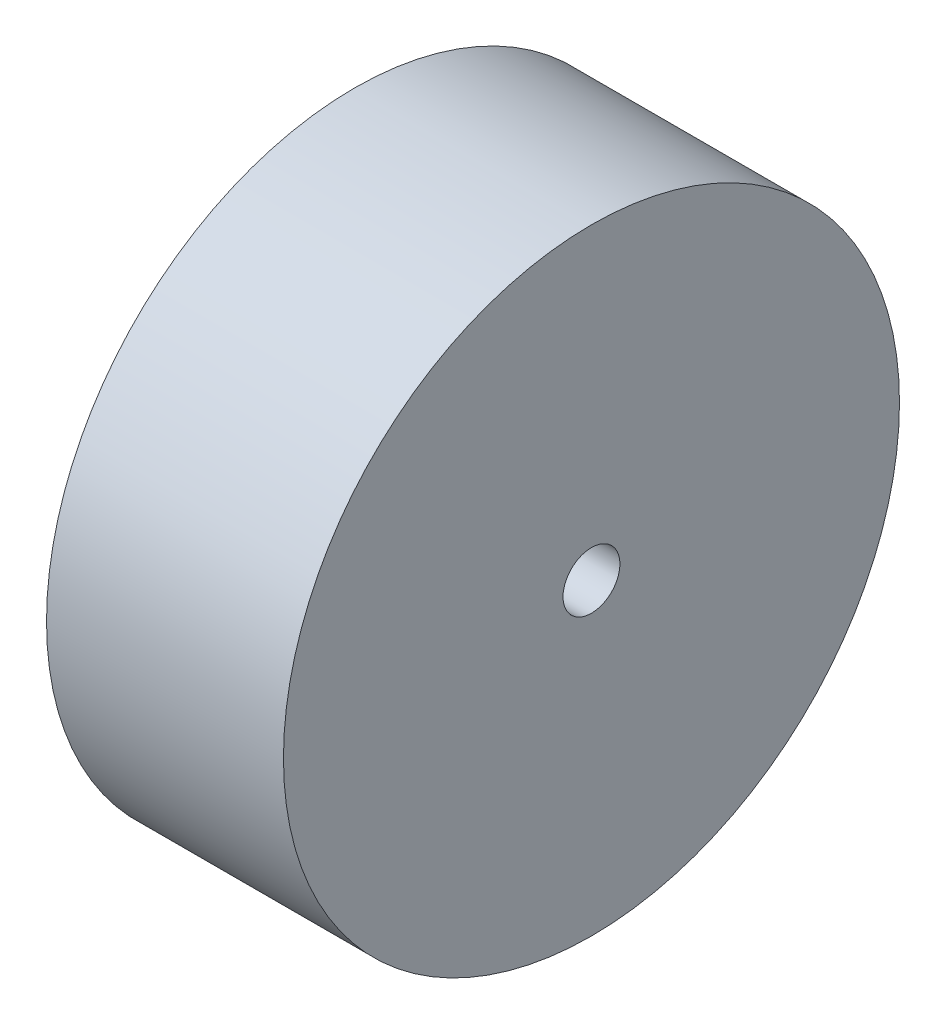
SolidWorks part; units mm, degrees
ref_plane "Front Plane" through (0, 0, 0) normal (0, 0, 1) x (1, 0, 0)
ref_plane "Top Plane" through (0, 0, 0) normal (0, 1, 0) x (1, 0, 0)
ref_plane "Right Plane" through (0, 0, 0) normal (1, 0, 0) x (0, 0, -1)
sketch "Sketch1" plane through (0, 0, 0) normal (1, 0, 0) x (0, 0, -1)
  circle A0 centre (0, 0) radius 32.5
  dimension "D1" = 65
extrude "Boss-Extrude1" add sketch "Sketch1" along normal blind 25
sketch "Sketch2" plane through (0, 0, 0) normal (-1, 0, 0) x (0, 0, 1)
  circle A0 centre (0, 0) radius 3
  dimension "D1" = 6
extrude "Cut-Extrude1" cut sketch "Sketch2" against normal through all
